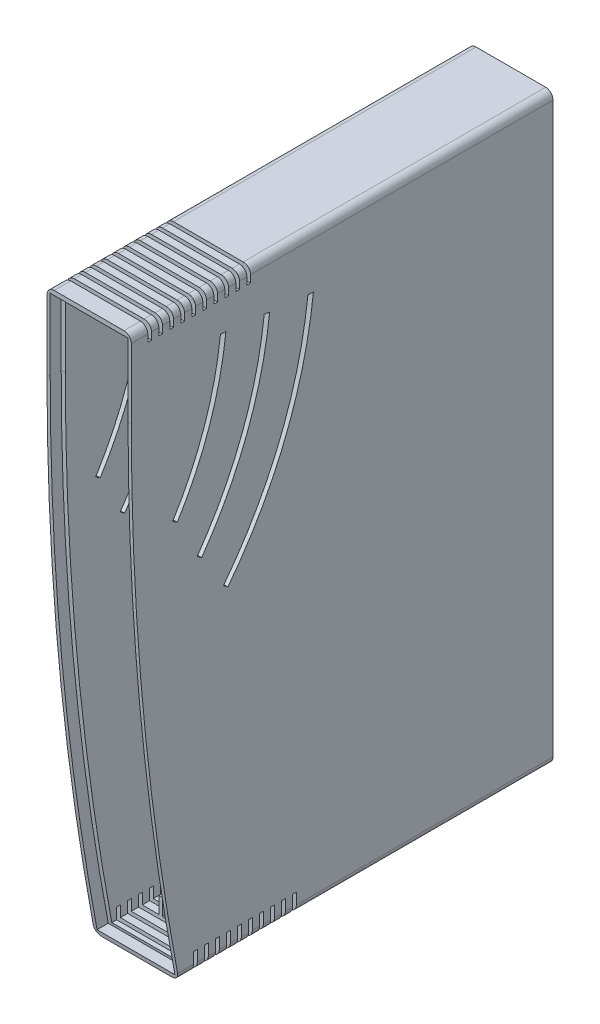
SolidWorks part; units mm, degrees
ref_plane "Front Plane" through (0, 0, 0) normal (0, 0, 1) x (1, 0, 0)
ref_plane "Top Plane" through (0, 0, 0) normal (0, 1, 0) x (1, 0, 0)
ref_plane "Right Plane" through (0, 0, 0) normal (1, 0, 0) x (0, 0, -1)
sketch "Sketch1" plane through (0, 0, 0) normal (0, 0, 1) x (1, 0, 0)
  line L1 (-11.5, -79.55) -> (11.5, -79.55)
  line L2 (-11.5, -79.55) -> (-11.5, 79.55)
  line L3 (-11.5, 79.55) -> (11.5, 79.55)
  line L4 (11.5, -79.55) -> (11.5, 79.55)
  line L5 (-11.5, -79.55) -> (11.5, 79.55) construction
  line L6 (-11.5, 79.55) -> (11.5, -79.55) construction
  point P0 (0, 0)
  dimension "D1" = 23
  dimension "D2" = 159.1
extrude "Boss-Extrude1" add sketch "Sketch1" along normal blind 115
shell "Shell1" thickness 2
sketch "Sketch2" plane through (11.5, 0, 0) normal (1, 0, 0) x (0, 0, -1)
  line L2 (-115, 79.55) -> (-115, 58.65)
  line L3 (-115, -79.55) -> (-115, 79.55) construction
  line L4 (-115, -79.55) -> (0, -79.55) construction
  arc A0 (-115, 58.65) -> (-102, -79.55) centre (626.0862, 58.65) ccw
  dimension "D1" = 20.9
  dimension "D2" = 13
extrude "Cut-Extrude1" cut sketch "Sketch2" along normal through all and the other way through all flip side to cut
fillet "Fillet1" radius 2 4 edges at (-11.5, -79.55, 51) (11.5, -79.55, 51) (-11.5, 79.55, 57.5) (11.5, 79.55, 57.5)
sketch "Sketch3" plane through (0, 79.55, 0) normal (0, 1, 0) x (1, 0, 0)
  line L0 (9.5, -115) -> (-9.5, -115) construction
  line L1 (-12.5, -109.5) -> (12.5, -109.5)
  line L2 (-12.5, -109.5) -> (-12.5, -110.5)
  line L3 (-12.5, -110.5) -> (12.5, -110.5)
  line L4 (12.5, -109.5) -> (12.5, -110.5)
  line L5 (-12.5, -109.5) -> (12.5, -110.5) construction
  line L6 (-12.5, -110.5) -> (12.5, -109.5) construction
  line L7 (0, -115) -> (0, -105.7345) construction
  point P0 (0, -110)
  dimension "D1" = 1
  dimension "D2" = 5
  dimension "D3" = 25
extrude "Cut-Extrude2" cut sketch "Sketch3" against normal blind 4
pattern_linear "LPattern1" count 10 spacing 3 along (0, 0, -1) of "Cut-Extrude2"
sketch "Sketch8" plane through (0, -79.55, 0) normal (0, -1, 0) x (1, 0, 0)
  line L0 (-9.5, 102) -> (9.5, 102) construction
  line L1 (-13.3258, 98) -> (14.3742, 98)
  line L2 (-13.3258, 98) -> (-13.3258, 97)
  line L3 (-13.3258, 97) -> (14.3742, 97)
  line L4 (14.3742, 98) -> (14.3742, 97)
  dimension "D1" = 4
  dimension "D2" = 1
extrude "Cut-Extrude4" cut sketch "Sketch8" against normal blind 5
pattern_linear "LPattern2" count 10 spacing 3 along (0, 0, -1) of "Cut-Extrude4"
sketch "Sketch5" plane through (-11.5, 0, 0) normal (-1, 0, 0) x (0, 0, 1)
  line L0 (65.347, 64.8235) -> (66.8382, 64.9865)
  line L1 (77.276, 66.1274) -> (78.7671, 66.2904)
  line L2 (89.2049, 67.4313) -> (90.6961, 67.5942)
  line L3 (88.6672, 6.884) -> (89.8554, 7.7995)
  line L5 (95.8273, 17.3757) -> (97.0496, 18.2452)
  line L6 (102.4576, 29.0608) -> (103.7315, 29.8528)
  arc A0 (90.6961, 67.5942) -> (103.7315, 29.8528) centre (180.1632, 77.3732) ccw
  arc A1 (89.2049, 67.4313) -> (102.4576, 29.0608) centre (180.1632, 77.3732) ccw
  arc A2 (77.276, 66.1274) -> (95.8273, 17.3757) centre (180.1632, 77.3732) ccw
  arc A3 (78.7671, 66.2904) -> (97.0496, 18.2452) centre (180.1632, 77.3732) ccw
  arc A4 (66.8382, 64.9865) -> (89.8554, 7.7995) centre (180.1632, 77.3732) ccw
  arc A5 (65.347, 64.8235) -> (88.6672, 6.884) centre (180.1632, 77.3732) ccw
  arc A6 (90.6961, 67.5942) -> (108.8676, 22.4466) centre (180.1632, 77.3732) ccw construction
  arc A7 (89.2049, 67.4313) -> (107.6794, 21.5311) centre (180.1632, 77.3732) ccw construction
  arc A8 (78.7671, 66.2904) -> (99.3615, 15.123) centre (180.1632, 77.3732) ccw construction
  arc A9 (77.276, 66.1274) -> (98.1733, 14.2076) centre (180.1632, 77.3732) ccw construction
  dimension "D6" = 90
  dimension "D4" = 12
  dimension "D1" = 1.5
  dimension "D2" = 12
  dimension "D3" = 1.5
  dimension "D5" = 1.5
extrude "Cut-Extrude3" cut sketch "Sketch5" against normal through all
ref_plane "Plane1" through (0, 0, 95) normal (0, 0, 1) x (1, 0, 0)
sketch "Sketch7" plane through (0, 0, 95) normal (0, 0, 1) x (1, 0, 0)
  line L0 (-5, 77.55) -> (-5, 73.05)
  line L1 (-5, 73.05) -> (-4, 73.05)
  line L2 (-4, 73.05) -> (-4, 77.55)
  line L3 (-4, 77.55) -> (-5, 77.55)
  line L4 (-2.2, 77.55) -> (-2.2, 73.05)
  line L5 (9.5, 77.55) -> (-9.5, 77.55) construction
  line L6 (-2.2, 73.05) -> (-1.2, 73.05)
  line L7 (-1.2, 73.05) -> (-1.2, 77.55)
  line L8 (-1.2, 77.55) -> (-2.2, 77.55)
  line L9 (-9.5, 77.55) -> (-9.5, -77.55) construction
  dimension "D1" = 5.5
  dimension "D2" = 1
  dimension "D3" = 1.8
  dimension "D4" = 4.5
  dimension "D5" = 1
extrude "Boss-Extrude3" add sketch "Sketch7" against normal blind 90
chamfer "Chamfer2" distance 0.5 angle 45 2 edges at (-2.2, 75.3, 95) (-4, 75.3, 95)
sketch "Sketch10" plane through (0, 0, 0) normal (1, 0, 0) x (0, 0, -1)
  line L1 (-131.7092, 78.35) -> (-112, 78.35)
  line L2 (-112, 58.65) -> (-112, 77.55)
  line L3 (-112, 58.65) -> (-112, 78.35)
  line L4 (-110.5, 77.55) -> (-115, 77.55) construction
  line L5 (-102.9238, -78.35) -> (-99.1739, -78.35)
  line L6 (-102.3768, -77.55) -> (-98, -77.55) construction
  line L7 (-131.7092, 78.35) -> (-102.9238, -78.35)
  arc A3 (-112, 58.65) -> (-99.4279, -76.9986) centre (626.0862, 58.65) ccw
  arc A4 (-112, 58.65) -> (-99.1739, -78.35) centre (626.0862, 58.65) ccw
  dimension "D2" = 0.8
  dimension "D3" = 0.8
  dimension "D1" = 3
extrude "Cut-Extrude6" cut sketch "Sketch10" against normal mid plane 21.222
sketch "Sketch11" plane through (0, 0, 2) normal (0, 0, 1) x (1, 0, 0)
  line L0 (9.5, -77.55) -> (-9.5, -77.55) construction
  line L1 (-5, -77.55) -> (-4, -77.55)
  line L2 (-5, -77.55) -> (-5, -73.05)
  line L3 (-5, -73.05) -> (-4, -73.05)
  line L4 (-4, -77.55) -> (-4, -73.05)
  line L5 (-9.5, -77.55) -> (9.5, -77.55) construction
  line L6 (-2.2, -77.55) -> (-1.2, -77.55)
  line L7 (-2.2, -77.55) -> (-2.2, -73.05)
  line L8 (-2.2, -73.05) -> (-1.2, -73.05)
  line L9 (-1.2, -77.55) -> (-1.2, -73.05)
  line L10 (-9.5, 77.55) -> (-9.5, -77.55) construction
  dimension "D1" = 4.5
  dimension "D2" = 4.5
  dimension "D3" = 5.5
  dimension "D4" = 1
  dimension "D5" = 1.8
  dimension "D6" = 1
extrude "Boss-Extrude6" add sketch "Sketch11" along normal blind 89
sketch "Sketch12" plane through (0, 0, 0) normal (0, 0, -1) x (-1, 0, 0)
  line L1 (-9.3, 71.48) -> (7, 71.48)
  line L2 (-9.3, 71.48) -> (-9.3, 46.98)
  line L3 (-9.3, 46.98) -> (7, 46.98)
  line L4 (7, 71.48) -> (7, 46.98)
  line L5 (-11.5, -77.55) -> (-11.5, 77.55) construction
  line L6 (11.5, 77.55) -> (11.5, -77.55) construction
  line L7 (2.6778, 71.12) -> (-7.55, 71.12) construction
  line L10 (7.25, 1.15) -> (-9.05, 1.15) construction
  line L11 (-9.4, 1.45) -> (7.6, 1.45)
  line L12 (-9.4, 1.45) -> (-9.4, -13.05)
  line L13 (-9.4, -13.05) -> (7.6, -13.05)
  line L14 (7.6, 1.45) -> (7.6, -13.05)
  line L16 (-9.05, -41.62) -> (7.25, -41.62) construction
  line L17 (-9.3, -41.27) -> (7.5, -41.27)
  line L18 (-9.3, -41.27) -> (-9.3, -71.47)
  line L19 (-9.3, -71.47) -> (7.5, -71.47)
  line L20 (7.5, -41.27) -> (7.5, -71.47)
  dimension "D1" = 2.2
  dimension "D2" = 4.5
  dimension "D3" = 24.5
  dimension "D4" = 0.36
  dimension "D5" = 2.1
  dimension "D6" = 14.5
  dimension "D7" = 17
  dimension "D8" = 0.3
  dimension "D9" = 2.2
  dimension "D10" = 4
  dimension "D11" = 30.2
  dimension "D12" = 0.35
extrude "Cut-Extrude7" cut sketch "Sketch12" against normal blind 2
